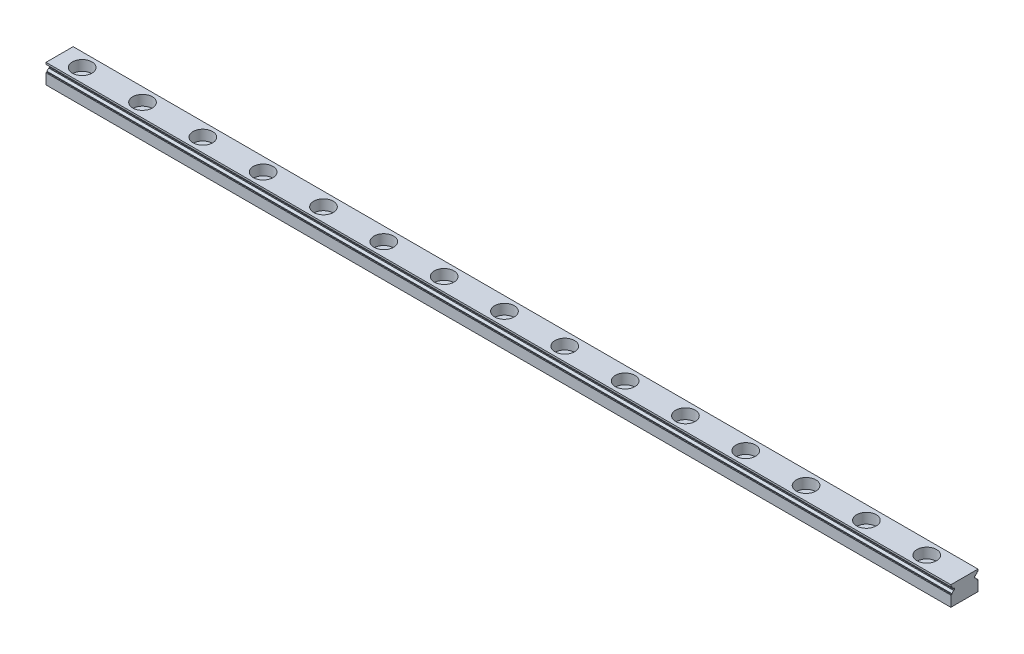
SolidWorks part; units mm, degrees
ref_plane "Plan de face" through (0, 0, 0) normal (0, 0, 1) x (1, 0, 0)
ref_plane "Plan de dessus" through (0, 0, 0) normal (0, 1, 0) x (1, 0, 0)
ref_plane "Plan de droite" through (0, 0, 0) normal (1, 0, 0) x (0, 0, -1)
sketch "Esquisse1" plane through (0, 0, 0) normal (1, 0, 0) x (0, 0, -1)
  line L0 (0, 0) -> (0, 10.8057) construction
  line L1 (-4.5, 0) -> (4.5, 0)
  line L2 (4.5, 0) -> (4.5, 3.5)
  line L3 (4.5, 3.5) -> (3.6, 4.4)
  line L4 (3.6, 4.4) -> (3.3, 4.4)
  line L5 (3.3, 4.4) -> (3.3, 5)
  line L6 (4.5, 5.9) -> (3.6, 5)
  line L7 (3.6, 5) -> (3.3, 5)
  line L8 (4.5, 5.9) -> (4.5, 6.5)
  line L9 (4.5, 6.5) -> (-4.5, 6.5)
  line L10 (3.3, 4.7) -> (8.4079, 4.7) construction
  line L11 (-4.5, 5.9) -> (-4.5, 6.5)
  line L12 (-4.5, 5.9) -> (-3.6, 5)
  line L13 (-3.6, 5) -> (-3.3, 5)
  line L14 (-3.3, 4.4) -> (-3.3, 5)
  line L15 (-3.6, 4.4) -> (-3.3, 4.4)
  line L16 (-4.5, 3.5) -> (-3.6, 4.4)
  line L17 (-4.5, 0) -> (-4.5, 3.5)
  point P10 (3.7233, 6.3621)
  point P15 (5.3844, 7.8689)
  point P16 (3.6, 5.2975)
  point P18 (0, 6.5)
  dimension "D1" = 6.5
  dimension "D2" = 9
  dimension "D3" = 0.6
  dimension "D4" = 1.2
  dimension "D5" = 2.4
  dimension "D6" = 4.7
extrude "Boss.-Extru.1" add sketch "Esquisse1" along normal blind 300
sketch "Esquisse2" plane through (0, 0, 0) normal (1, 0, 0) x (0, 0, -1)
  line L0 (3.3, 5) -> (3.6, 5) construction
  line L1 (4.5, 5.9) -> (4.2, 5.9)
  line L2 (4.5, 5.9) -> (4.5, 3.5)
  line L3 (4.5, 3.5) -> (4.2, 3.5)
  line L4 (4.2, 5.9) -> (4.2, 3.5)
  line L5 (0, 0) -> (0, 7.1139) construction
  line L6 (-4.5, 5.9) -> (-4.2, 5.9)
  line L7 (-4.5, 5.9) -> (-4.5, 3.5)
  line L8 (-4.5, 3.5) -> (-4.2, 3.5)
  line L9 (-4.2, 5.9) -> (-4.2, 3.5)
extrude "Enlèv. mat.-Extru.1" cut sketch "Esquisse2" along normal through all
hole_wizard "Chambrage pour vis à tête hexagonale M31" positions "Esquisse3" profile "Esquisse4" counterbore size "M3" standard "ISO" end condition through all
sketch "Esquisse3" plane through (0, 6.5, 0) normal (0, 1, 0) x (1, 0, 0)
  line L0 (0, 4.5) -> (0, -4.5) construction
  point P0 (7.5, 0)
  point P3 (0, 0)
  point P6 (0, 0)
  dimension "D1" = 7.5
sketch "Esquisse4" plane through (7.5, 6.5, 0) normal (1, 0, 0) x (0, 0, 1)
  line L0 (0, 0) -> (0, 6.5)
  line L1 (0, 6.5) -> (1.2294, 6.5)
  line L3 (1.2294, 6.5) -> (1.2294, 3.4)
  line L4 (1.2294, 3.4) -> (3.25, 3.4)
  line L5 (3.25, 3.4) -> (3.25, 0)
  line L7 (3.25, 0) -> (0, 0)
  line L11 (0, -6.35) -> (0, 107.95) construction
  dimension "Diamètre du perçage jusqu'au prochain" = 2.4588
  dimension "Profondeur du perçage jusqu'au prochain" = 6.5
  dimension "Diamètre du chambrage" = 6.5
  dimension "Profondeur du chambrage" = 3.4
pattern_linear "Répétition linéaire1" count 15 spacing 20 along (1, 0, 0) of "Chambrage pour vis à tête hexagonale M31"
